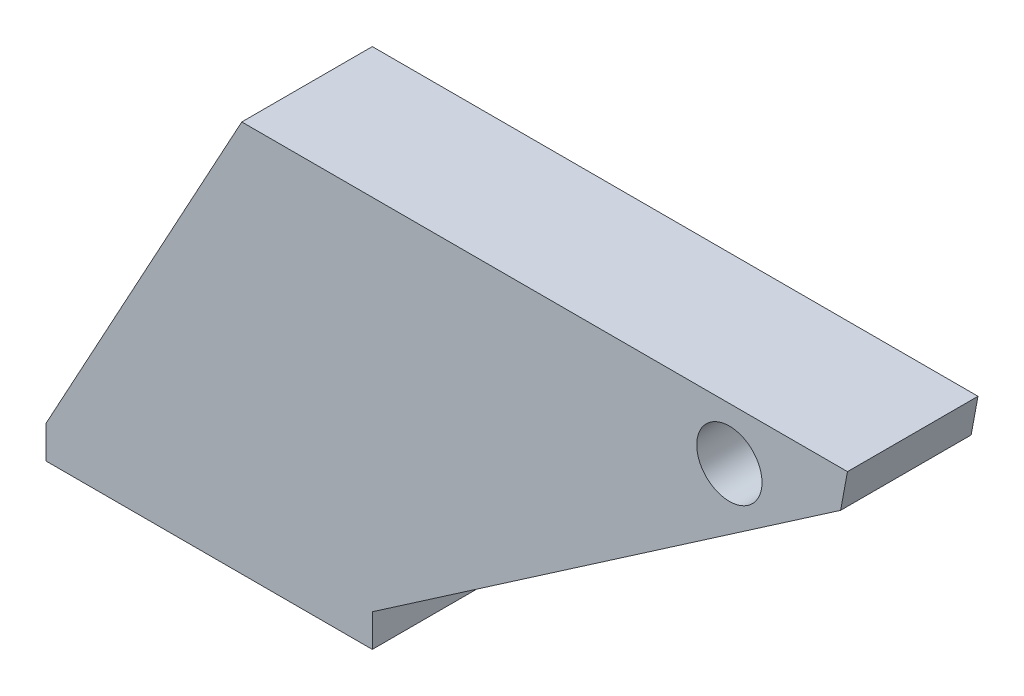
SolidWorks part; units mm, degrees
ref_plane "前视基准面" through (0, 0, 0) normal (0, 0, 1) x (1, 0, 0)
ref_plane "上视基准面" through (0, 0, 0) normal (0, 1, 0) x (1, 0, 0)
ref_plane "右视基准面" through (0, 0, 0) normal (1, 0, 0) x (0, 0, -1)
sketch "草图1" plane through (0, 0, 0) normal (0, 0, 1) x (1, 0, 0)
  line L0 (-58.9541, -2.0079) -> (-58.9541, -7.0079)
  line L1 (-58.9541, -7.0079) -> (-8.9541, -7.0079)
  line L2 (-8.9541, -7.0079) -> (-8.9541, -2.0079)
  line L3 (-8.9541, -2.0079) -> (71.0459, 52.9921)
  line L4 (71.0459, 52.9921) -> (-28.9541, 52.9921)
  line L5 (-28.9541, 52.9921) -> (-58.9541, -2.0079)
  circle A1 centre (45.7566, 44.9921) radius 5
  dimension "D8" = 8
  dimension "D1" = 50
  dimension "D2" = 60
  dimension "D3" = 5
  dimension "D4" = 5
  dimension "D5" = 100
  dimension "D6" = 130
extrude "凸台-拉伸1" add sketch "草图1" along normal blind 20
chamfer "倒角1" distance 10 angle 45 1 edges at (71.0459, 52.9921, 10)
sketch "草图2" plane through (0, -7.0079, 0) normal (0, -1, 0) x (1, 0, 0)
  line L0 (-8.9541, 20) -> (-8.9541, 0) construction
  line L1 (-58.9541, 0) -> (-8.9541, 0) construction
  circle A0 centre (-23.9541, 10) radius 5
  dimension "D1" = 15
  dimension "D2" = 10
extrude "切除-拉伸1" cut sketch "草图2" against normal blind 10
